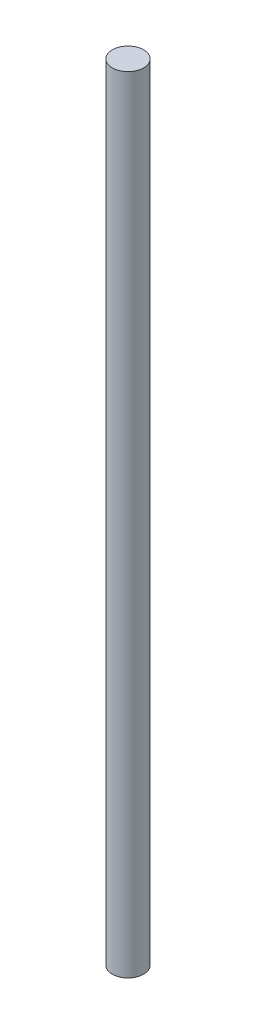
SolidWorks part; units mm, degrees
other "Markup1"
sketch "Sketch2" plane through (-5, 125, 5) normal (-0.5306, 0.0842, 0.8434) x (0.847, 0.0158, 0.5313)
ref_plane "Front Plane" through (0, 0, 0) normal (0, 0, 1) x (1, 0, 0)
ref_plane "Top Plane" through (0, 0, 0) normal (0, 1, 0) x (1, 0, 0)
ref_plane "Right Plane" through (0, 0, 0) normal (1, 0, 0) x (0, 0, -1)
sketch "Sketch1" plane through (0, 0, 0) normal (0, 1, 0) x (1, 0, 0)
  circle A0 centre (0, 0) radius 5
  dimension "D1" = 10
extrude "Boss-Extrude1" add sketch "Sketch1" along normal mid plane 250
